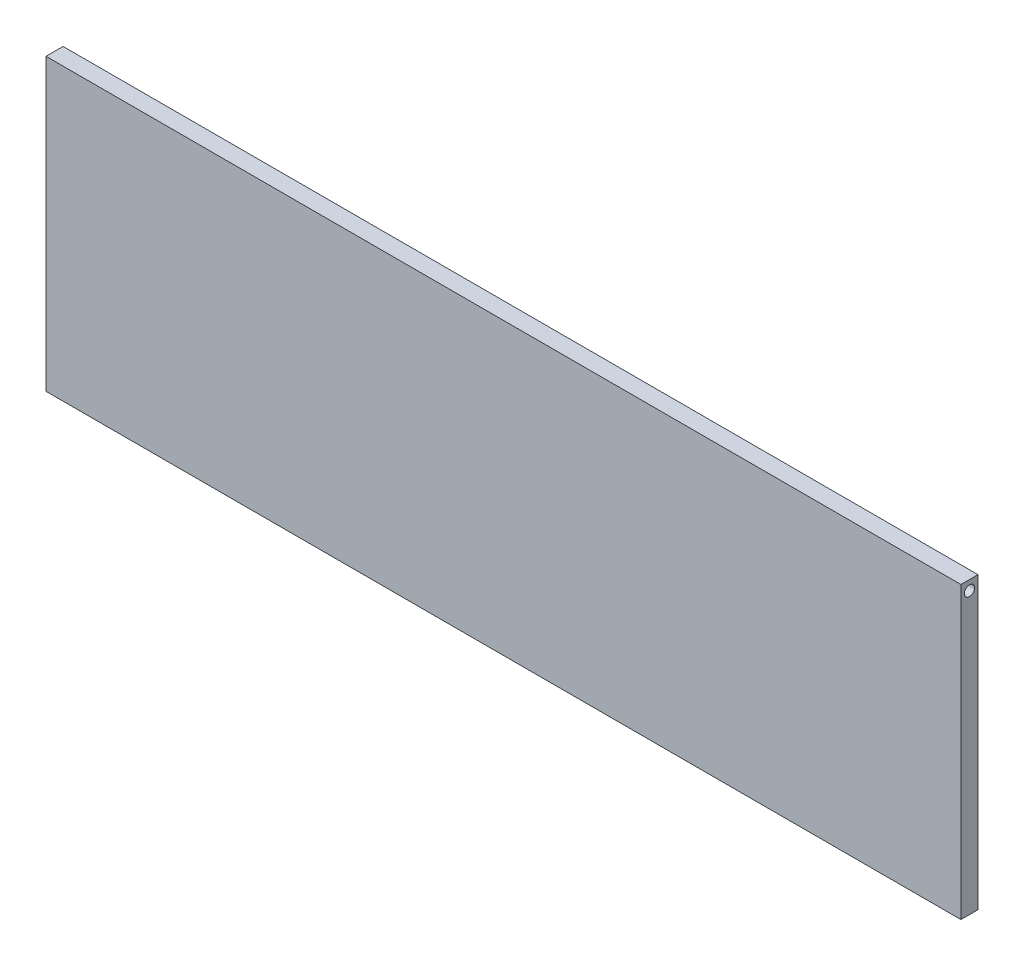
SolidWorks part; units mm, degrees
ref_plane "Front Plane" through (0, 0, 0) normal (0, 0, 1) x (1, 0, 0)
ref_plane "Top Plane" through (0, 0, 0) normal (0, 1, 0) x (1, 0, 0)
ref_plane "Right Plane" through (0, 0, 0) normal (1, 0, 0) x (0, 0, -1)
sketch "Sketch1" plane through (0, 0, 0) normal (0, 0, 1) x (1, 0, 0)
  line L1 (-161.8238, 47.2435) -> (106.1762, 47.2435)
  line L2 (-161.8238, 47.2435) -> (-161.8238, -37.7565)
  line L3 (-161.8238, -37.7565) -> (106.1762, -37.7565)
  line L4 (106.1762, 47.2435) -> (106.1762, -37.7565)
  dimension "D1" = 268
  dimension "D2" = 85
extrude "Boss-Extrude1" add sketch "Sketch1" along normal blind 5
sketch "Sketch2" plane through (106.1762, 0, 0) normal (1, 0, 0) x (0, 0, -1)
  line L0 (-2.5, 47.2435) -> (-2.5, 40.2366) construction
  line L1 (-5, 47.2435) -> (0, 47.2435) construction
  circle A0 centre (-2.5, 44.4206) radius 1.5
  dimension "D1" = 3
extrude "Cut-Extrude1" cut sketch "Sketch2" against normal through all
